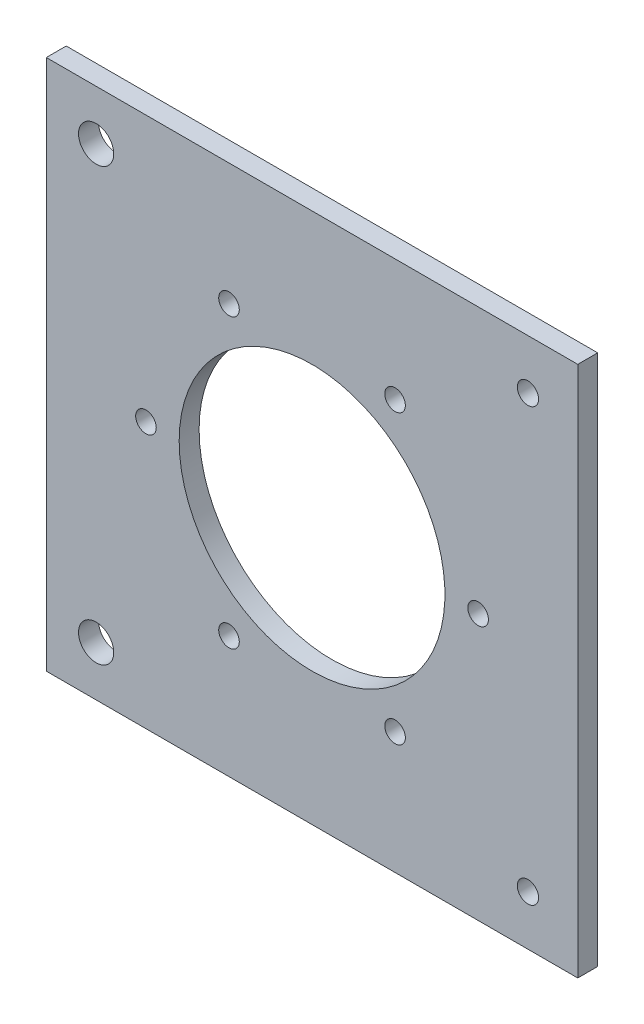
SolidWorks part; units mm, degrees
ref_plane "前视基准面" through (0, 0, 0) normal (0, 0, 1) x (1, 0, 0)
ref_plane "上视基准面" through (0, 0, 0) normal (0, 1, 0) x (1, 0, 0)
ref_plane "右视基准面" through (0, 0, 0) normal (1, 0, 0) x (0, 0, -1)
other "Configuration Table"
sketch "草图1" plane through (0, 0, 0) normal (0, 0, 1) x (1, 0, 0)
  line L1 (-40, -40) -> (40, -40)
  line L2 (-40, -40) -> (-40, 40)
  line L3 (-40, 40) -> (40, 40)
  line L4 (40, -40) -> (40, 40)
  line L5 (-40, -40) -> (40, 40) construction
  line L6 (-40, 40) -> (40, -40) construction
  line L7 (-32.5, -32.5) -> (32.5, -32.5)
  line L8 (-32.5, -32.5) -> (-32.5, 32.5)
  line L9 (-32.5, 32.5) -> (32.5, 32.5)
  line L10 (32.5, -32.5) -> (32.5, 32.5)
  line L11 (-32.5, -32.5) -> (32.5, 32.5) construction
  line L12 (-32.5, 32.5) -> (32.5, -32.5) construction
  circle A0 centre (-32.5, 32.5) radius 2.65
  circle A1 centre (-32.5, -32.5) radius 2.65
  circle A2 centre (32.5, 32.5) radius 1.6
  circle A3 centre (32.5, -32.5) radius 1.6
  circle A4 centre (0, 0) radius 18
  point P0 (0, 0)
  point P6 (0, 0)
  dimension "D5" = 5.3
  dimension "D6" = 5.3
  dimension "D7" = 3.2
  dimension "D8" = 3.2
  dimension "D9" = 36
  dimension "D1" = 80
  dimension "D2" = 80
  dimension "D3" = 65
  dimension "D4" = 65
extrude "凸台-拉伸1" add sketch "草图1" along normal blind 4 contours A3 L10 A2 L9 A0 L8 A1 L7 A4 | L1 L4 L3 L2 A3 L7 A1 L8 A0 L9 A2 L10
sketch "草图2" plane through (0, 0, 4) normal (0, 0, 1) x (1, 0, 0)
  line L0 (0, -1000) -> (0, 49000) construction
  line L1 (-32.5, -32.5) -> (32.5, -32.5)
  line L2 (-32.5, -32.5) -> (-32.5, 32.5)
  line L3 (-32.5, 32.5) -> (32.5, 32.5)
  line L4 (32.5, -32.5) -> (32.5, 32.5)
  line L5 (-32.5, -32.5) -> (32.5, 32.5) construction
  line L6 (-32.5, 32.5) -> (32.5, -32.5) construction
  line L7 (0, 0) -> (25000, -43301.2702) construction
  circle A0 centre (0, 0) radius 25
  circle A1 centre (-12.5, 21.6506) radius 1.55
  circle A2 centre (12.5, 21.6506) radius 1.55
  circle A3 centre (25, 0) radius 1.55
  circle A4 centre (12.5, -21.6506) radius 1.55
  circle A5 centre (-12.5, -21.6506) radius 1.55
  circle A6 centre (-25, 0) radius 1.55
  point P27 (0, 0)
  dimension "D1" = 50
  dimension "D3" = 3.1
  dimension "D2" = 30
  dimension "D4" = 6
extrude "切除-拉伸1" cut sketch "草图2" against normal through all contours A6 | A5 | A1 | A2 | A3 | A4
sketch "草图4" plane through (0, 0, 0) normal (0, 0, -1) x (-1, 0, 0)
  circle A0 centre (0, 0) radius 20
  dimension "D1" = 40
extrude "切除-拉伸2" cut sketch "草图4" against normal through all
sketch "草图5" plane through (0, 0, 0) normal (0, 0, -1) x (-1, 0, 0)
  line L1 (-57.9649, 53.0857) -> (83.7271, 53.0857)
  line L2 (-57.9649, 53.0857) -> (-57.9649, -64.9259)
  line L3 (-57.9649, -64.9259) -> (83.7271, -64.9259)
  line L4 (83.7271, 53.0857) -> (83.7271, -64.9259)
extrude "切除-拉伸3" cut sketch "草图5" against normal blind 1
